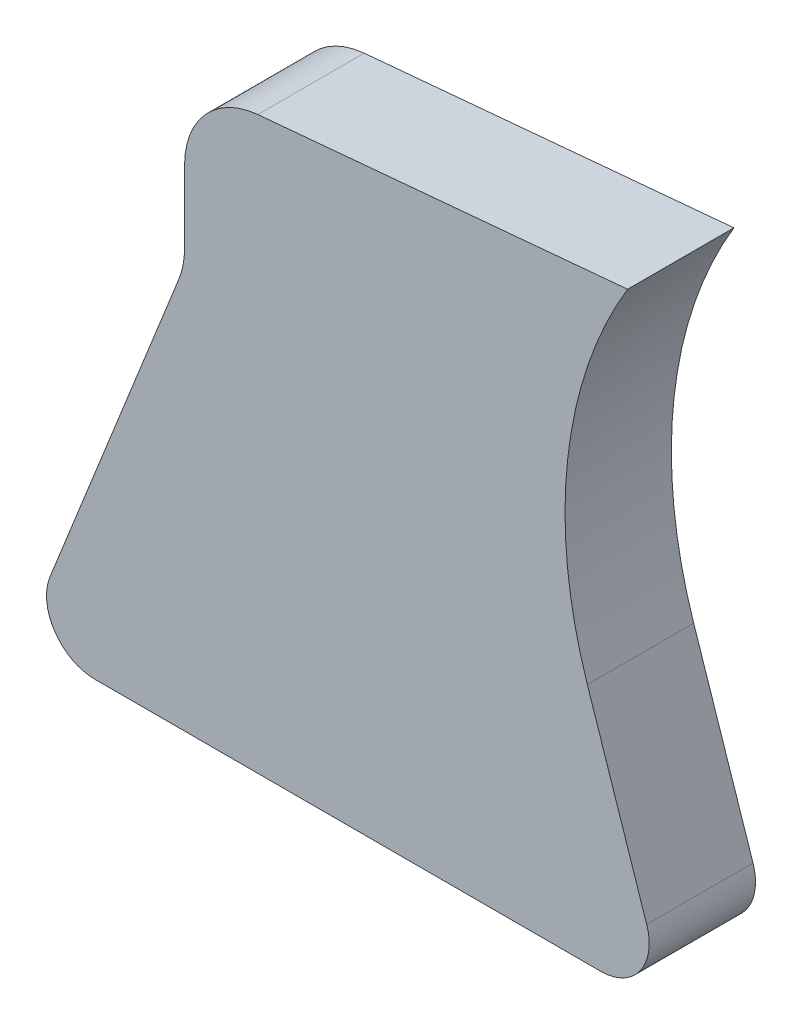
SolidWorks part; units mm, degrees
material "Alloy Steel"
ref_plane "Front Plane" through (0, 0, 0) normal (0, 0, 1) x (1, 0, 0)
ref_plane "Top Plane" through (0, 0, 0) normal (0, 1, 0) x (1, 0, 0)
ref_plane "Right Plane" through (0, 0, 0) normal (1, 0, 0) x (0, 0, -1)
sketch "Sketch1" plane through (0, 0, 0) normal (0, 0, 1) x (1, 0, 0)
  line L0 (0, 0) -> (12.7, 31.75)
  line L1 (12.7, 31.75) -> (12.7, 44.45)
  line L2 (12.7, 44.45) -> (47.625, 47.625)
  line L3 (44.45, 19.05) -> (50.8, 0)
  line L4 (50.8, 0) -> (0, 0)
  arc A0 (47.625, 47.625) -> (44.45, 19.05) centre (76.9937, 29.8979) ccw
  dimension "D1" = 50.8
  dimension "D2" = 12.7
  dimension "D3" = 31.75
  dimension "D4" = 19.05
  dimension "D5" = 15.875
  dimension "D6" = 12.7
  dimension "D7" = 3.175
  dimension "D8" = 6.35
extrude "Extrude1" add sketch "Sketch1" along normal blind 8.382
fillet "Fillet1" radius 6.35 2 edges at (12.7, 44.45, 4.191) (12.7, 31.75, 4.191)
fillet "Fillet2" radius 3.81 2 edges at (50.8, 0, 4.191) (0, 0, 4.191)
